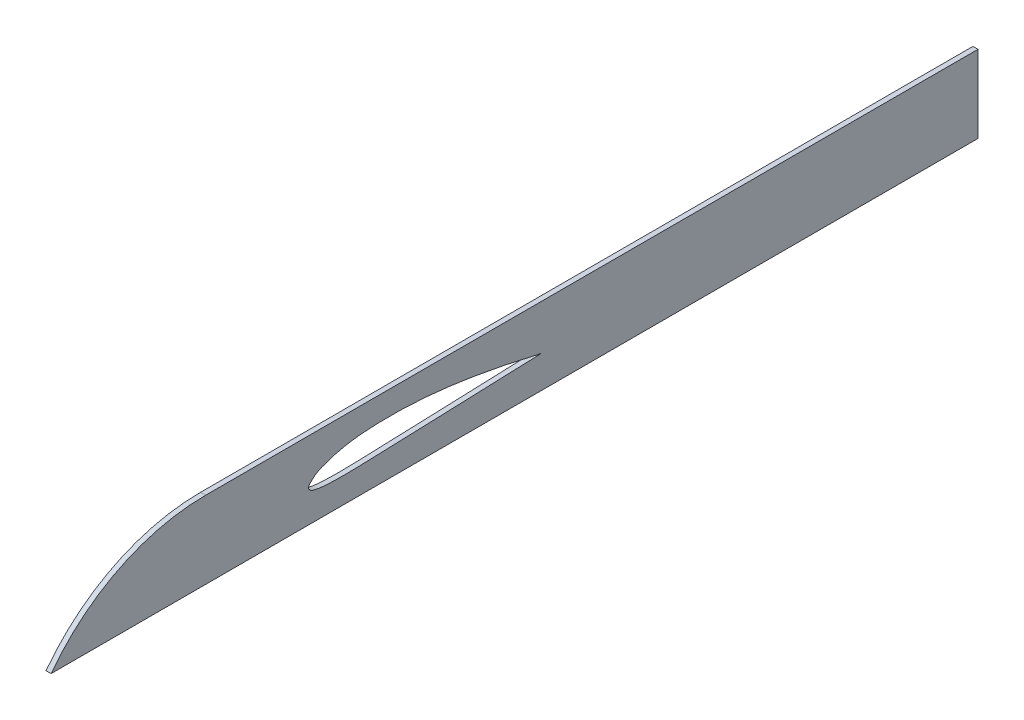
SolidWorks part; units mm, degrees
ref_plane "Front Plane" through (0, 0, 0) normal (0, 0, 1) x (1, 0, 0)
ref_plane "Top Plane" through (0, 0, 0) normal (0, 1, 0) x (1, 0, 0)
ref_plane "Right Plane" through (0, 0, 0) normal (1, 0, 0) x (0, 0, -1)
sketch "Fuselage Boundary" plane through (0, 0, 0) normal (1, 0, 0) x (0, 0, -1)
  line L0 (0, 0) -> (914.4, 0)
  line L1 (914.4, 0) -> (914.4, 76.2)
  line L2 (914.4, 76.2) -> (152.4, 76.2)
  arc A0 (0, 0) -> (152.4, 76.2) centre (152.4, -114.3) cw
  point P2 (0, 0)
  point P6 (154.5493, 76.2)
  dimension "D1" = 914.4
  dimension "D2" = 76.2
  dimension "D3" = 762
curve "Curve1"
  spline degree 3 poles (25.4044, -0.098, 0) (25.3998, 0, 0) (25.4043, 0.0994, 0) (25.1091, 0.0483, 0) (24.9016, 0.1413, 0) (24.6358, 0.1944, 0) (24.3007, 0.274, 0) (23.8758, 0.3711, 0) (23.3684, 0.4855, 0) (22.8602, 0.5972, 0) (22.3523, 0.7066, 0) (21.8442, 0.8129, 0) (21.3366, 0.9182, 0) (20.8279, 1.0153, 0) (20.3206, 1.1166, 0) (19.8119, 1.2083, 0) (19.3046, 1.3044, 0) (18.7961, 1.3918, 0) (18.2885, 1.4797, 0) (17.7799, 1.5588, 0) (17.2725, 1.6422, 0) (16.7641, 1.717, 0) (16.2564, 1.792, 0) (15.7481, 1.8591, 0) (15.2405, 1.9272, 0) (14.7321, 1.9839, 0) (14.2241, 2.0397, 0) (13.7164, 2.0948, 0) (13.2081, 2.1386, 0) (12.7002, 2.1827, 0) (12.1923, 2.2216, 0) (11.684, 2.2504, 0) (11.1761, 2.2793, 0) (10.6681, 2.3026, 0) (10.1601, 2.3179, 0) (9.652, 2.3248, 0) (9.144, 2.3275, 0) (8.636, 2.3249, 0) (8.128, 2.3173, 0) (7.6199, 2.3047, 0) (7.1119, 2.2865, 0) (6.6037, 2.2652, 0) (6.0956, 2.2316, 0) (5.5874, 2.1891, 0) (5.0791, 2.1335, 0) (4.5706, 2.0628, 0) (4.0623, 1.9738, 0) (3.5544, 1.8662, 0) (3.0456, 1.7452, 0) (2.5363, 1.6038, 0) (2.0284, 1.4343, 0) (1.6038, 1.2776, 0) (1.2665, 1.1266, 0) (1.0113, 0.9939, 0) (0.753, 0.8388, 0) (0.5146, 0.6581, 0) (0.3345, 0.4868, 0) (0.1997, 0.3461, 0) (0.1124, 0.2451, 0) (0.0549, 0.1583, 0) (0.0273, 0.1009, 0) (0.0097, 0.0517, 0) (-0.0067, -0.0192, 0) (0.0004, -0.0931, 0) (0.028, -0.1565, 0) (0.0544, -0.2079, 0) (0.1114, -0.2825, 0) (0.1965, -0.3623, 0) (0.3301, -0.453, 0) (0.5195, -0.5264, 0) (0.7614, -0.5738, 0) (1.0151, -0.6243, 0) (1.2694, -0.662, 0) (1.608, -0.6987, 0) (2.0317, -0.7256, 0) (2.5399, -0.7476, 0) (3.0479, -0.7645, 0) (3.556, -0.7663, 0) (4.064, -0.7727, 0) (4.572, -0.7606, 0) (5.0801, -0.7568, 0) (5.588, -0.7383, 0) (6.0961, -0.7249, 0) (6.604, -0.7056, 0) (7.1121, -0.6894, 0) (7.6199, -0.6668, 0) (8.1281, -0.6514, 0) (8.6359, -0.629, 0) (9.144, -0.6122, 0) (9.6521, -0.5952, 0) (10.1599, -0.5732, 0) (10.668, -0.5563, 0) (11.1761, -0.5393, 0) (11.6839, -0.5173, 0) (12.192, -0.5004, 0) (12.7001, -0.4834, 0) (13.2079, -0.4614, 0) (13.716, -0.4445, 0) (14.2241, -0.4276, 0) (14.7319, -0.4056, 0) (15.24, -0.3886, 0) (15.7481, -0.3717, 0) (16.2559, -0.3497, 0) (16.764, -0.3327, 0) (17.2721, -0.3159, 0) (17.7799, -0.2935, 0) (18.2881, -0.278, 0) (18.7959, -0.2556, 0) (19.304, -0.2388, 0) (19.8121, -0.2218, 0) (20.3199, -0.1998, 0) (20.828, -0.1829, 0) (21.3361, -0.1659, 0) (21.8439, -0.1439, 0) (22.352, -0.127, 0) (22.86, -0.11, 0) (23.3681, -0.0882, 0) (23.8755, -0.0707, 0) (24.3009, -0.0583, 0) (24.6354, -0.0409, 0) (24.9019, -0.0416, 0) (25.1087, 0.009, 0) (25.4044, -0.098, 0) (25.3998, 0, 0) (25.4043, 0.0994, 0) knots -0.010078 -0.005187 -0.000293 0 0.000293 0.005322 0.010339 0.015367 0.020384 0.030418 0.040442 0.050454 0.060457 0.070449 0.080431 0.090394 0.100357 0.110302 0.120247 0.130174 0.140093 0.149997 0.1599 0.169788 0.179669 0.189537 0.199398 0.209241 0.219079 0.228912 0.23873 0.248544 0.258351 0.268147 0.277941 0.287729 0.297513 0.307293 0.317072 0.326851 0.33663 0.346412 0.356197 0.365986 0.375786 0.3856 0.395437 0.405312 0.415239 0.425231 0.435288 0.445443 0.45574 0.466202 0.471563 0.477074 0.482801 0.488943 0.494304 0.49714 0.500195 0.501999 0.503136 0.503863 0.505014 0.507325 0.507961 0.50901 0.510653 0.513351 0.515711 0.519942 0.524959 0.529936 0.53488 0.539799 0.549602 0.55939 0.569174 0.578953 0.588732 0.598512 0.608292 0.618075 0.627858 0.637643 0.647428 0.657215 0.667 0.676786 0.686571 0.696356 0.706143 0.715928 0.725712 0.735499 0.745284 0.755069 0.764856 0.77464 0.784425 0.794212 0.803997 0.813782 0.823568 0.833353 0.843138 0.852925 0.862709 0.872496 0.882281 0.892066 0.901853 0.911637 0.921422 0.931209 0.940994 0.950779 0.960565 0.97035 0.980135 0.985028 0.989922 0.994813 0.999707 1 1.000293 1.005322 1.010339 periodic
sketch "Sketch2" plane through (0, 0, 0) normal (0, 0, 1) x (1, 0, 0)
  spline S0 degree 3 poles (25.4044, -0.098) (25.3998, 0) (25.4043, 0.0994) (25.1091, 0.0483) (24.9016, 0.1413) (24.6358, 0.1944) (24.3007, 0.274) (23.8758, 0.3711) (23.3684, 0.4855) (22.8602, 0.5972) (22.3523, 0.7066) (21.8442, 0.8129) (21.3366, 0.9182) (20.8279, 1.0153) (20.3206, 1.1166) (19.8119, 1.2083) (19.3046, 1.3044) (18.7961, 1.3918) (18.2885, 1.4797) (17.7799, 1.5588) (17.2725, 1.6422) (16.7641, 1.717) (16.2564, 1.792) (15.7481, 1.8591) (15.2405, 1.9272) (14.7321, 1.9839) (14.2241, 2.0397) (13.7164, 2.0948) (13.2081, 2.1386) (12.7002, 2.1827) (12.1923, 2.2216) (11.684, 2.2504) (11.1761, 2.2793) (10.6681, 2.3026) (10.1601, 2.3179) (9.652, 2.3248) (9.144, 2.3275) (8.636, 2.3249) (8.128, 2.3173) (7.6199, 2.3047) (7.1119, 2.2865) (6.6037, 2.2652) (6.0956, 2.2316) (5.5874, 2.1891) (5.0791, 2.1335) (4.5706, 2.0628) (4.0623, 1.9738) (3.5544, 1.8662) (3.0456, 1.7452) (2.5363, 1.6038) (2.0284, 1.4343) (1.6038, 1.2776) (1.2665, 1.1266) (1.0113, 0.9939) (0.753, 0.8388) (0.5146, 0.6581) (0.3345, 0.4868) (0.1997, 0.3461) (0.1124, 0.2451) (0.0549, 0.1583) (0.0273, 0.1009) (0.0097, 0.0517) (-0.0067, -0.0192) (0.0004, -0.0931) (0.028, -0.1565) (0.0544, -0.2079) (0.1114, -0.2825) (0.1965, -0.3623) (0.3301, -0.453) (0.5195, -0.5264) (0.7614, -0.5738) (1.0151, -0.6243) (1.2694, -0.662) (1.608, -0.6987) (2.0317, -0.7256) (2.5399, -0.7476) (3.0479, -0.7645) (3.556, -0.7663) (4.064, -0.7727) (4.572, -0.7606) (5.0801, -0.7568) (5.588, -0.7383) (6.0961, -0.7249) (6.604, -0.7056) (7.1121, -0.6894) (7.6199, -0.6668) (8.1281, -0.6514) (8.6359, -0.629) (9.144, -0.6122) (9.6521, -0.5952) (10.1599, -0.5732) (10.668, -0.5563) (11.1761, -0.5393) (11.6839, -0.5173) (12.192, -0.5004) (12.7001, -0.4834) (13.2079, -0.4614) (13.716, -0.4445) (14.2241, -0.4276) (14.7319, -0.4056) (15.24, -0.3886) (15.7481, -0.3717) (16.2559, -0.3497) (16.764, -0.3327) (17.2721, -0.3159) (17.7799, -0.2935) (18.2881, -0.278) (18.7959, -0.2556) (19.304, -0.2388) (19.8121, -0.2218) (20.3199, -0.1998) (20.828, -0.1829) (21.3361, -0.1659) (21.8439, -0.1439) (22.352, -0.127) (22.86, -0.11) (23.3681, -0.0882) (23.8755, -0.0707) (24.3009, -0.0583) (24.6354, -0.0409) (24.9019, -0.0416) (25.1087, 0.009) (25.4044, -0.098) (25.3998, 0) (25.4043, 0.0994) knots -0.010078 -0.005187 -0.000293 0 0.000293 0.005322 0.010339 0.015367 0.020384 0.030418 0.040442 0.050454 0.060457 0.070449 0.080431 0.090394 0.100357 0.110302 0.120247 0.130174 0.140093 0.149997 0.1599 0.169788 0.179669 0.189537 0.199398 0.209241 0.219079 0.228912 0.23873 0.248544 0.258351 0.268147 0.277941 0.287729 0.297513 0.307293 0.317072 0.326851 0.33663 0.346412 0.356197 0.365986 0.375786 0.3856 0.395437 0.405312 0.415239 0.425231 0.435288 0.445443 0.45574 0.466202 0.471563 0.477074 0.482801 0.488943 0.494304 0.49714 0.500195 0.501999 0.503136 0.503863 0.505014 0.507325 0.507961 0.50901 0.510653 0.513351 0.515711 0.519942 0.524959 0.529936 0.53488 0.539799 0.549602 0.55939 0.569174 0.578953 0.588732 0.598512 0.608292 0.618075 0.627858 0.637643 0.647428 0.657215 0.667 0.676786 0.686571 0.696356 0.706143 0.715928 0.725712 0.735499 0.745284 0.755069 0.764856 0.77464 0.784425 0.794212 0.803997 0.813782 0.823568 0.833353 0.843138 0.852925 0.862709 0.872496 0.882281 0.892066 0.901853 0.911637 0.921422 0.931209 0.940994 0.950779 0.960565 0.97035 0.980135 0.985028 0.989922 0.994813 0.999707 1 1.000293 1.005322 1.010339 only from (25.4, 0) to (25.4, 0) construction
  spline S1 degree 3 poles (25.4044, -0.098) (25.3998, 0) (25.4043, 0.0994) (25.1091, 0.0483) (24.9016, 0.1413) (24.6358, 0.1944) (24.3007, 0.274) (23.8758, 0.3711) (23.3684, 0.4855) (22.8602, 0.5972) (22.3523, 0.7066) (21.8442, 0.8129) (21.3366, 0.9182) (20.8279, 1.0153) (20.3206, 1.1166) (19.8119, 1.2083) (19.3046, 1.3044) (18.7961, 1.3918) (18.2885, 1.4797) (17.7799, 1.5588) (17.2725, 1.6422) (16.7641, 1.717) (16.2564, 1.792) (15.7481, 1.8591) (15.2405, 1.9272) (14.7321, 1.9839) (14.2241, 2.0397) (13.7164, 2.0948) (13.2081, 2.1386) (12.7002, 2.1827) (12.1923, 2.2216) (11.684, 2.2504) (11.1761, 2.2793) (10.6681, 2.3026) (10.1601, 2.3179) (9.652, 2.3248) (9.144, 2.3275) (8.636, 2.3249) (8.128, 2.3173) (7.6199, 2.3047) (7.1119, 2.2865) (6.6037, 2.2652) (6.0956, 2.2316) (5.5874, 2.1891) (5.0791, 2.1335) (4.5706, 2.0628) (4.0623, 1.9738) (3.5544, 1.8662) (3.0456, 1.7452) (2.5363, 1.6038) (2.0284, 1.4343) (1.6038, 1.2776) (1.2665, 1.1266) (1.0113, 0.9939) (0.753, 0.8388) (0.5146, 0.6581) (0.3345, 0.4868) (0.1997, 0.3461) (0.1124, 0.2451) (0.0549, 0.1583) (0.0273, 0.1009) (0.0097, 0.0517) (-0.0067, -0.0192) (0.0004, -0.0931) (0.028, -0.1565) (0.0544, -0.2079) (0.1114, -0.2825) (0.1965, -0.3623) (0.3301, -0.453) (0.5195, -0.5264) (0.7614, -0.5738) (1.0151, -0.6243) (1.2694, -0.662) (1.608, -0.6987) (2.0317, -0.7256) (2.5399, -0.7476) (3.0479, -0.7645) (3.556, -0.7663) (4.064, -0.7727) (4.572, -0.7606) (5.0801, -0.7568) (5.588, -0.7383) (6.0961, -0.7249) (6.604, -0.7056) (7.1121, -0.6894) (7.6199, -0.6668) (8.1281, -0.6514) (8.6359, -0.629) (9.144, -0.6122) (9.6521, -0.5952) (10.1599, -0.5732) (10.668, -0.5563) (11.1761, -0.5393) (11.6839, -0.5173) (12.192, -0.5004) (12.7001, -0.4834) (13.2079, -0.4614) (13.716, -0.4445) (14.2241, -0.4276) (14.7319, -0.4056) (15.24, -0.3886) (15.7481, -0.3717) (16.2559, -0.3497) (16.764, -0.3327) (17.2721, -0.3159) (17.7799, -0.2935) (18.2881, -0.278) (18.7959, -0.2556) (19.304, -0.2388) (19.8121, -0.2218) (20.3199, -0.1998) (20.828, -0.1829) (21.3361, -0.1659) (21.8439, -0.1439) (22.352, -0.127) (22.86, -0.11) (23.3681, -0.0882) (23.8755, -0.0707) (24.3009, -0.0583) (24.6354, -0.0409) (24.9019, -0.0416) (25.1087, 0.009) (25.4044, -0.098) (25.3998, 0) (25.4043, 0.0994) knots -0.010078 -0.005187 -0.000293 0 0.000293 0.005322 0.010339 0.015367 0.020384 0.030418 0.040442 0.050454 0.060457 0.070449 0.080431 0.090394 0.100357 0.110302 0.120247 0.130174 0.140093 0.149997 0.1599 0.169788 0.179669 0.189537 0.199398 0.209241 0.219079 0.228912 0.23873 0.248544 0.258351 0.268147 0.277941 0.287729 0.297513 0.307293 0.317072 0.326851 0.33663 0.346412 0.356197 0.365986 0.375786 0.3856 0.395437 0.405312 0.415239 0.425231 0.435288 0.445443 0.45574 0.466202 0.471563 0.477074 0.482801 0.488943 0.494304 0.49714 0.500195 0.501999 0.503136 0.503863 0.505014 0.507325 0.507961 0.50901 0.510653 0.513351 0.515711 0.519942 0.524959 0.529936 0.53488 0.539799 0.549602 0.55939 0.569174 0.578953 0.588732 0.598512 0.608292 0.618075 0.627858 0.637643 0.647428 0.657215 0.667 0.676786 0.686571 0.696356 0.706143 0.715928 0.725712 0.735499 0.745284 0.755069 0.764856 0.77464 0.784425 0.794212 0.803997 0.813782 0.823568 0.833353 0.843138 0.852925 0.862709 0.872496 0.882281 0.892066 0.901853 0.911637 0.921422 0.931209 0.940994 0.950779 0.960565 0.97035 0.980135 0.985028 0.989922 0.994813 0.999707 1 1.000293 1.005322 1.010339 only from (25.4, 0) to (25.4, 0)
sketch "Airfoil Cut" plane through (0, 0, 0) normal (1, 0, 0) x (0, 0, -1)
  line L0 (0, 0) -> (254, 0) construction
  line L1 (0, 0) -> (914.4, 0) construction
  line L2 (254, 0) -> (254, 31.75) construction
  line L3 (254, 31.75) -> (482.6002, 31.75) construction
  spline S0 degree 3 poles (482.6387, 30.8682) (482.598, 31.7502) (482.6403, 32.6448) (479.9825, 32.1874) (478.1157, 33.0271) (475.7243, 33.5079) (472.7094, 34.2279) (468.8866, 35.1062) (464.3207, 36.141) (459.7485, 37.1517) (455.1781, 38.1409) (450.6065, 39.1034) (446.0392, 40.0567) (441.4615, 40.9351) (436.8974, 41.8525) (432.3195, 42.6829) (427.7548, 43.5534) (423.1799, 44.3451) (418.6123, 45.1414) (414.0355, 45.8592) (409.4697, 46.6151) (404.8952, 47.2929) (400.3267, 47.9733) (395.7525, 48.5827) (391.1852, 49.2008) (386.6099, 49.7162) (382.0385, 50.2245) (377.47, 50.7254) (372.8952, 51.1251) (368.3249, 51.5271) (363.754, 51.8828) (359.1802, 52.1471) (354.6093, 52.4126) (350.0376, 52.627) (345.4653, 52.7702) (340.8928, 52.8378) (336.3206, 52.8677) (331.7483, 52.8497) (327.176, 52.7863) (322.6036, 52.6782) (318.0314, 52.5199) (313.4573, 52.3329) (308.8843, 52.036) (304.3097, 51.6587) (299.7342, 51.1635) (295.1575, 50.5326) (290.5817, 49.7377) (286.0098, 48.7742) (281.4286, 47.6903) (276.8436, 46.4235) (272.2712, 44.903) (268.4482, 43.4969) (265.4103, 42.1415) (263.1123, 40.9504) (260.7862, 39.5571) (258.6387, 37.9334) (257.0157, 36.3931) (255.8013, 35.1283) (255.0149, 34.2201) (254.496, 33.4394) (254.2474, 32.923) (254.0878, 32.4805) (253.9399, 31.8427) (254.0032, 31.178) (254.2508, 30.6063) (254.488, 30.1436) (255.0003, 29.4721) (255.7648, 28.753) (256.9664, 27.9352) (258.6702, 27.2727) (260.8466, 26.8435) (263.1293, 26.3864) (265.4177, 26.0442) (268.4648, 25.7102) (272.278, 25.4641) (276.8512, 25.2605) (281.4233, 25.103) (285.9962, 25.0815) (290.5685, 25.0188) (295.1402, 25.1222) (299.7133, 25.1508) (304.2844, 25.3126) (308.8572, 25.4279) (313.4287, 25.596) (318.0017, 25.7366) (322.5726, 25.9344) (327.1461, 26.0679) (331.7171, 26.2644) (336.2899, 26.4105) (340.8626, 26.5579) (345.4337, 26.7506) (350.0064, 26.8977) (354.5792, 27.0448) (359.1503, 27.2376) (363.723, 27.3847) (368.2957, 27.5318) (372.8668, 27.7245) (377.4396, 27.8717) (382.0123, 28.0188) (386.5834, 28.2115) (391.1562, 28.3586) (395.7289, 28.5058) (400.3, 28.6985) (404.8727, 28.8458) (409.4455, 28.992) (414.0165, 29.1883) (418.59, 29.3222) (423.1609, 29.5185) (427.7337, 29.6647) (432.3064, 29.8121) (436.8775, 30.0048) (441.4503, 30.1519) (446.023, 30.299) (450.5941, 30.4918) (455.1669, 30.6388) (459.7393, 30.7863) (464.3119, 30.9777) (468.8788, 31.1299) (472.7075, 31.2365) (475.7182, 31.39) (478.117, 31.3812) (479.9789, 31.8338) (482.6387, 30.8682) (482.598, 31.7502) (482.6403, 32.6448) knots -0.010078 -0.005187 -0.000293 0 0.000293 0.005322 0.010339 0.015367 0.020384 0.030418 0.040442 0.050454 0.060457 0.070449 0.080431 0.090394 0.100357 0.110302 0.120247 0.130174 0.140093 0.149997 0.1599 0.169788 0.179669 0.189537 0.199398 0.209241 0.219079 0.228912 0.23873 0.248544 0.258351 0.268147 0.277941 0.287729 0.297513 0.307293 0.317072 0.326851 0.33663 0.346412 0.356197 0.365986 0.375786 0.3856 0.395437 0.405312 0.415239 0.425231 0.435288 0.445443 0.45574 0.466202 0.471563 0.477074 0.482801 0.488943 0.494304 0.49714 0.500195 0.501999 0.503136 0.503863 0.505014 0.507325 0.507961 0.50901 0.510653 0.513351 0.515711 0.519942 0.524959 0.529936 0.53488 0.539799 0.549602 0.55939 0.569174 0.578953 0.588732 0.598512 0.608292 0.618075 0.627858 0.637643 0.647428 0.657215 0.667 0.676786 0.686571 0.696356 0.706143 0.715928 0.725712 0.735499 0.745284 0.755069 0.764856 0.77464 0.784425 0.794212 0.803997 0.813782 0.823568 0.833353 0.843138 0.852925 0.862709 0.872496 0.882281 0.892066 0.901853 0.911637 0.921422 0.931209 0.940994 0.950779 0.960565 0.97035 0.980135 0.985028 0.989922 0.994813 0.999707 1 1.000293 1.005322 1.010339 only from (482.6002, 31.75) to (482.6002, 31.75)
  dimension "D1" = 254
  dimension "D2" = 31.75
  dimension "D3" = 228.6002
sketch "Landing Gear Cut" plane through (0, 0, 0) normal (1, 0, 0) x (0, 0, -1)
  line L0 (0, 0) -> (584.2, 0) construction
  line L1 (0, 0) -> (914.4, 0) construction
  line L2 (584.2, 0) -> (584.2, 25.4) construction
  line L3 (584.2, 25.4) -> (608.0682, 16.7127)
  line L4 (608.0682, 16.7127) -> (609.4363, 20.4715)
  line L5 (609.4363, 20.4715) -> (599.3816, 24.1311)
  line L6 (585.5681, 29.1588) -> (584.2, 25.4)
  line L7 (595.6228, 25.4992) -> (599.9664, 37.4333)
  line L8 (599.9664, 37.4333) -> (603.7252, 36.0652)
  line L9 (603.7252, 36.0652) -> (599.3816, 24.1311)
  line L10 (595.6228, 25.4992) -> (585.5681, 29.1588)
  dimension "D1" = 584.2
  dimension "D2" = 25.4
  dimension "D3" = 25.4
  dimension "D4" = 4
  dimension "D5" = 10.7
  dimension "D6" = 12.7
  dimension "D7" = 4
sketch "Motor Mount Cut" plane through (0, 0, 0) normal (1, 0, 0) x (0, 0, -1)
  line L0 (914.4, 76.2) -> (152.4, 76.2) construction
  line L3 (755.65, 67.2) -> (717.55, 67.2)
  line L4 (755.65, 67.2) -> (755.65, 71.2)
  line L5 (755.65, 71.2) -> (717.55, 71.2)
  line L6 (717.55, 67.2) -> (717.55, 71.2)
  dimension "D1" = 158.75
  dimension "D2" = 4
  dimension "D3" = 38.1
  dimension "D4" = 5
extrude "Boss-Extrude1" add sketch "Fuselage Boundary" along normal blind 5
extrude "Cut-Extrude3" cut sketch "Airfoil Cut" along normal up to surface (5 mm away) contours S0 up to face at (5, 42.5971, -493.0515)
extrude "Cut-Extrude4" [suppressed] cut sketch "Landing Gear Cut" along normal up to surface (5 mm away) contours L10 L6 L3 L4 L5 L9 L8 L7
extrude "Cut-Extrude5" [suppressed] cut sketch "Motor Mount Cut" along normal up to surface (5 mm away) contours L5 L6 L3 L4
sketch "Sketch3" plane through (5, 0, 0) normal (1, 0, 0) x (0, 0, -1)
  line L0 (254.0943, 32.4713) -> (254.0943, 0) construction
  line L1 (0, 0) -> (914.4, 0) construction
  line L2 (254.0943, 0) -> (0.0943, 0) construction
  spline S0 degree 3 poles (482.6387, 30.8682) (482.598, 31.7502) (482.6403, 32.6448) (479.9825, 32.1874) (478.1157, 33.0271) (475.7243, 33.5079) (472.7094, 34.2279) (468.8866, 35.1062) (464.3207, 36.141) (459.7485, 37.1517) (455.1781, 38.1409) (450.6065, 39.1034) (446.0392, 40.0567) (441.4615, 40.9351) (436.8974, 41.8525) (432.3195, 42.6829) (427.7548, 43.5534) (423.1799, 44.3451) (418.6123, 45.1414) (414.0355, 45.8592) (409.4697, 46.6151) (404.8952, 47.2929) (400.3267, 47.9733) (395.7525, 48.5827) (391.1852, 49.2008) (386.6099, 49.7162) (382.0385, 50.2245) (377.47, 50.7254) (372.8952, 51.1251) (368.3249, 51.5271) (363.754, 51.8828) (359.1802, 52.1471) (354.6093, 52.4126) (350.0376, 52.627) (345.4653, 52.7702) (340.8928, 52.8378) (336.3206, 52.8677) (331.7483, 52.8497) (327.176, 52.7863) (322.6036, 52.6782) (318.0314, 52.5199) (313.4573, 52.3329) (308.8843, 52.036) (304.3097, 51.6587) (299.7342, 51.1635) (295.1575, 50.5326) (290.5817, 49.7377) (286.0098, 48.7742) (281.4286, 47.6903) (276.8436, 46.4235) (272.2712, 44.903) (268.4482, 43.4969) (265.4103, 42.1415) (263.1123, 40.9504) (260.7862, 39.5571) (258.6387, 37.9334) (257.0157, 36.3931) (255.8013, 35.1283) (255.0149, 34.2201) (254.496, 33.4394) (254.2474, 32.923) (254.0878, 32.4805) (253.9399, 31.8427) (254.0032, 31.178) (254.2508, 30.6063) (254.488, 30.1436) (255.0003, 29.4721) (255.7648, 28.753) (256.9664, 27.9352) (258.6702, 27.2727) (260.8466, 26.8435) (263.1293, 26.3864) (265.4177, 26.0442) (268.4648, 25.7102) (272.278, 25.4641) (276.8512, 25.2605) (281.4233, 25.103) (285.9962, 25.0815) (290.5685, 25.0188) (295.1402, 25.1222) (299.7133, 25.1508) (304.2844, 25.3126) (308.8572, 25.4279) (313.4287, 25.596) (318.0017, 25.7366) (322.5726, 25.9344) (327.1461, 26.0679) (331.7171, 26.2644) (336.2899, 26.4105) (340.8626, 26.5579) (345.4337, 26.7506) (350.0064, 26.8977) (354.5792, 27.0448) (359.1503, 27.2376) (363.723, 27.3847) (368.2957, 27.5318) (372.8668, 27.7245) (377.4396, 27.8717) (382.0123, 28.0188) (386.5834, 28.2115) (391.1562, 28.3586) (395.7289, 28.5058) (400.3, 28.6985) (404.8727, 28.8458) (409.4455, 28.992) (414.0165, 29.1883) (418.59, 29.3222) (423.1609, 29.5185) (427.7337, 29.6647) (432.3064, 29.8121) (436.8775, 30.0048) (441.4503, 30.1519) (446.023, 30.299) (450.5941, 30.4918) (455.1669, 30.6388) (459.7393, 30.7863) (464.3119, 30.9777) (468.8788, 31.1299) (472.7075, 31.2365) (475.7182, 31.39) (478.117, 31.3812) (479.9789, 31.8338) (482.6387, 30.8682) (482.598, 31.7502) (482.6403, 32.6448) knots -0.010078 -0.005187 -0.000293 0 0.000293 0.005322 0.010339 0.015367 0.020384 0.030418 0.040442 0.050454 0.060457 0.070449 0.080431 0.090394 0.100357 0.110302 0.120247 0.130174 0.140093 0.149997 0.1599 0.169788 0.179669 0.189537 0.199398 0.209241 0.219079 0.228912 0.23873 0.248544 0.258351 0.268147 0.277941 0.287729 0.297513 0.307293 0.317072 0.326851 0.33663 0.346412 0.356197 0.365986 0.375786 0.3856 0.395437 0.405312 0.415239 0.425231 0.435288 0.445443 0.45574 0.466202 0.471563 0.477074 0.482801 0.488943 0.494304 0.49714 0.500195 0.501999 0.503136 0.503863 0.505014 0.507325 0.507961 0.50901 0.510653 0.513351 0.515711 0.519942 0.524959 0.529936 0.53488 0.539799 0.549602 0.55939 0.569174 0.578953 0.588732 0.598512 0.608292 0.618075 0.627858 0.637643 0.647428 0.657215 0.667 0.676786 0.686571 0.696356 0.706143 0.715928 0.725712 0.735499 0.745284 0.755069 0.764856 0.77464 0.784425 0.794212 0.803997 0.813782 0.823568 0.833353 0.843138 0.852925 0.862709 0.872496 0.882281 0.892066 0.901853 0.911637 0.921422 0.931209 0.940994 0.950779 0.960565 0.97035 0.980135 0.985028 0.989922 0.994813 0.999707 1 1.000293 1.005322 1.010339 only from (482.6002, 31.75) to (482.6002, 31.75) construction
  dimension "D1" = 254
